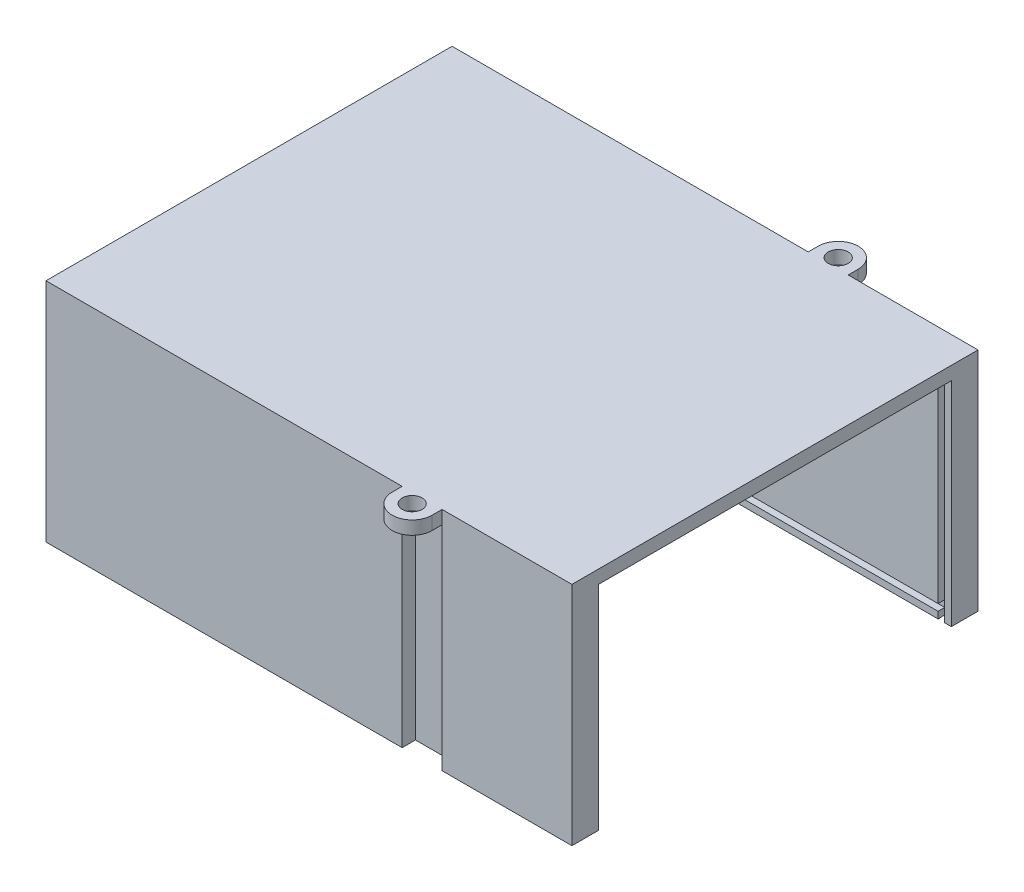
SolidWorks part; units mm, degrees
ref_plane "前视基准面" through (0, 0, 0) normal (0, 0, 1) x (1, 0, 0)
ref_plane "上视基准面" through (0, 0, 0) normal (0, 1, 0) x (1, 0, 0)
ref_plane "右视基准面" through (0, 0, 0) normal (1, 0, 0) x (0, 0, -1)
other "Configuration Table"
sketch "草图1" plane through (0, 0, 0) normal (0, 1, 0) x (1, 0, 0)
  line L0 (14, 28.5) -> (14, 32)
  line L1 (39.5, 28.5) -> (-39.5, 28.5)
  line L2 (39.5, 28.5) -> (39.5, -28.5)
  line L3 (39.5, -28.5) -> (-39.5, -28.5)
  line L4 (-39.5, 28.5) -> (-39.5, -28.5)
  line L5 (39.5, 28.5) -> (-39.5, -28.5) construction
  line L6 (39.5, -28.5) -> (-39.5, 28.5) construction
  line L7 (35.5, 24.5) -> (-35.5, 24.5)
  line L8 (35.5, 24.5) -> (35.5, -24.5)
  line L9 (35.5, -24.5) -> (-35.5, -24.5)
  line L10 (-35.5, 24.5) -> (-35.5, -24.5)
  line L11 (35.5, 24.5) -> (-35.5, -24.5) construction
  line L12 (35.5, -24.5) -> (-35.5, 24.5) construction
  line L13 (20, 32) -> (20, 28.5)
  line L14 (20, 28.5) -> (14, 28.5)
  line L15 (0, 0) -> (-50000, 0) construction
  line L16 (20, -32) -> (20, -28.5)
  line L17 (14, -28.5) -> (14, -32)
  line L18 (20, -28.5) -> (14, -28.5)
  arc A0 (14, 32) -> (20, 32) centre (17, 32) cw
  arc A1 (14, -32) -> (20, -32) centre (17, -32) ccw
  circle A2 centre (17, 32) radius 1.5
  circle A3 centre (17, -32) radius 1.5
  point P0 (0, 0)
  point P6 (0, 0)
  dimension "D6" = 3
  dimension "D7" = 3
  dimension "D8" = 3
  dimension "D1" = 71
  dimension "D2" = 49
  dimension "D3" = 79
  dimension "D4" = 57
  dimension "D5" = 3.5
  dimension "D9" = 19.5
extrude "凸台-拉伸1" add sketch "草图1" along normal blind 2 contours L7 L10 L9 L8 | L1 L4 L3 L2 L10 L7 L8 L9 | L17 A1 L16 L3 A3 | A0 L0 L1 L13 A2
sketch "草图2" plane through (0, 0, 0) normal (0, 1, 0) x (1, 0, 0)
  line L0 (-39.5, 26.5) -> (39.5, 26.5)
  line L1 (-39.5, 28.5) -> (-39.5, -28.5) construction
  line L2 (39.5, 28.5) -> (39.5, -28.5) construction
  line L3 (39.5, 26.5) -> (39.5, 28.5)
  line L4 (39.5, 28.5) -> (-39.5, 28.5)
  line L5 (-39.5, 28.5) -> (-39.5, 26.5)
  line L6 (0, 0) -> (-50000, 0) construction
  line L7 (39.5, -26.5) -> (39.5, -28.5)
  line L8 (39.5, -28.5) -> (-39.5, -28.5)
  line L9 (-39.5, -28.5) -> (-39.5, -26.5)
  line L10 (-39.5, -26.5) -> (39.5, -26.5)
  dimension "D1" = 2
extrude "凸台-拉伸2" add sketch "草图2" against normal blind 32
sketch "草图3" plane through (0, 0, 0) normal (0, 1, 0) x (1, 0, 0)
  line L0 (38.5, 27.5) -> (37.5, 27.5)
  line L1 (37.5, 27.5) -> (37.5, -27.5)
  line L2 (37.5, -27.5) -> (38.5, -27.5)
  line L3 (38.5, -27.5) -> (38.5, 27.5)
  line L4 (39.5, 28.5) -> (39.5, -28.5) construction
  line L5 (39.5, 28.5) -> (20, 28.5) construction
  line L6 (39.5, -28.5) -> (20, -28.5) construction
  dimension "D1" = 1
  dimension "D2" = 1
  dimension "D3" = 1
  dimension "D4" = 1
extrude "切除-拉伸1" cut sketch "草图3" against normal through all and the other way blind 1
sketch "草图4" plane through (0, 0, 0) normal (1, 0, 0) x (0, 0, -1)
  line L0 (-26.5, -31) -> (-27.5, -31)
  line L1 (-26.5, -32) -> (-26.5, 0) construction
  line L2 (-27.5, -31) -> (-27.5, -30)
  line L3 (-27.5, -30) -> (-26.5, -30)
  line L4 (-26.5, -30) -> (-26.5, -31)
  line L5 (0, 0) -> (0, 50000) construction
  line L6 (26.5, 0) -> (-26.5, 0) construction
  line L7 (-28.5, -32) -> (-26.5, -32) construction
  line L8 (26.5, -31) -> (27.5, -31)
  line L9 (27.5, -30) -> (26.5, -30)
  line L10 (26.5, -30) -> (26.5, -31)
  line L11 (27.5, -31) -> (27.5, -30)
  point P10 (0, 0)
  point P11 (-27, -31)
  dimension "D1" = 1
  dimension "D2" = 1
  dimension "D3" = 1
extrude "切除-拉伸2" cut sketch "草图4" against normal through all and the other way blind 37.5
sketch "草图5" plane through (0, 0, 0) normal (0, 1, 0) x (1, 0, 0)
  line L0 (14, 28.5) -> (14, 30.5)
  line L1 (14, 28.5) -> (14, 32) construction
  line L2 (-39.5, 28.5) -> (-39.5, 30.5)
  line L3 (-39.5, 30.5) -> (14, 30.5)
  line L4 (-39.5, 28.5) -> (14, 28.5)
  line L5 (0, 0) -> (-50000, 0) construction
  line L6 (14, -28.5) -> (14, -30.5)
  line L7 (-39.5, -30.5) -> (14, -30.5)
  line L8 (-39.5, -28.5) -> (-39.5, -30.5)
  line L9 (-39.5, -28.5) -> (14, -28.5)
  line L10 (20, 30.5) -> (20, 28.5)
  line L11 (20, 32) -> (20, 28.5) construction
  line L12 (20, 28.5) -> (39.5, 28.5)
  line L13 (39.5, 28.5) -> (39.5, 30.5)
  line L14 (39.5, 30.5) -> (20, 30.5)
  line L15 (39.5, -28.5) -> (39.5, -30.5)
  line L16 (39.5, -30.5) -> (20, -30.5)
  line L17 (20, -32) -> (20, -28.5) construction
  line L18 (20, -30.5) -> (20, -28.5)
  line L19 (20, -28.5) -> (39.5, -28.5)
  dimension "D1" = 2
  dimension "D2" = 2
extrude "凸台-拉伸3" add sketch "草图5" against normal up to surface (32 mm away) and the other way blind 2 up to face at (19, -32, 27.25)
